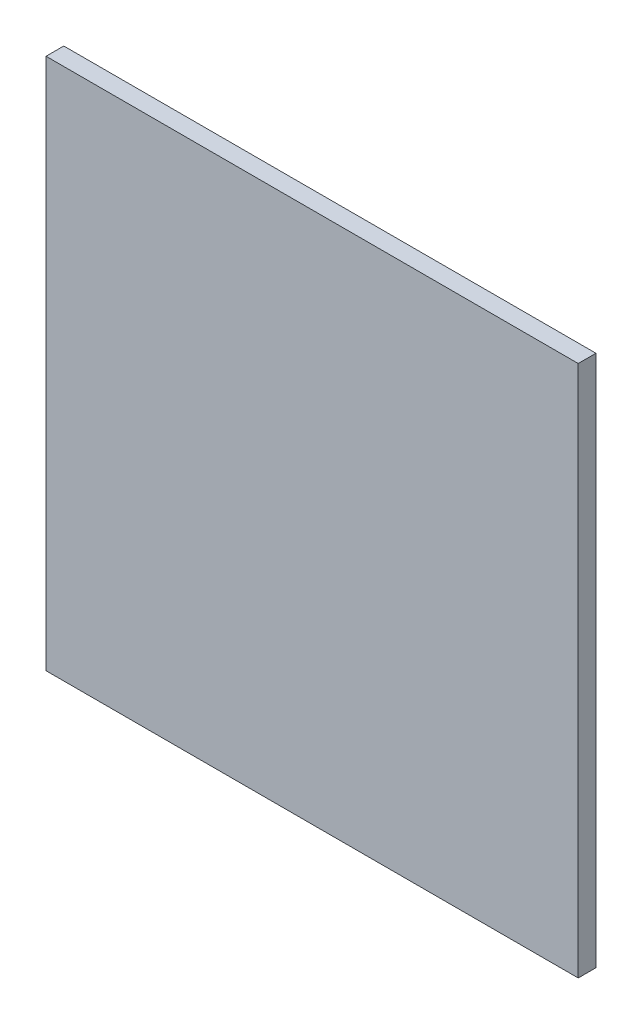
SolidWorks part; units mm, degrees
ref_plane "Alzado" through (0, 0, 0) normal (0, 0, 1) x (1, 0, 0)
ref_plane "Planta" through (0, 0, 0) normal (0, 1, 0) x (1, 0, 0)
ref_plane "Vista lateral" through (0, 0, 0) normal (1, 0, 0) x (0, 0, -1)
sketch "Croquis1" plane through (0, 0, 0) normal (0, 0, 1) x (1, 0, 0)
  line L1 (-7.5, 7.5) -> (7.5, 7.5)
  line L2 (-7.5, 7.5) -> (-7.5, -7.5)
  line L3 (-7.5, -7.5) -> (7.5, -7.5)
  line L4 (7.5, 7.5) -> (7.5, -7.5)
  line L5 (-7.5, 7.5) -> (7.5, -7.5) construction
  line L6 (-7.5, -7.5) -> (7.5, 7.5) construction
  point P0 (0, 0)
  dimension "D1" = 15
extrude "Saliente-Extruir1" add sketch "Croquis1" along normal blind 0.5
